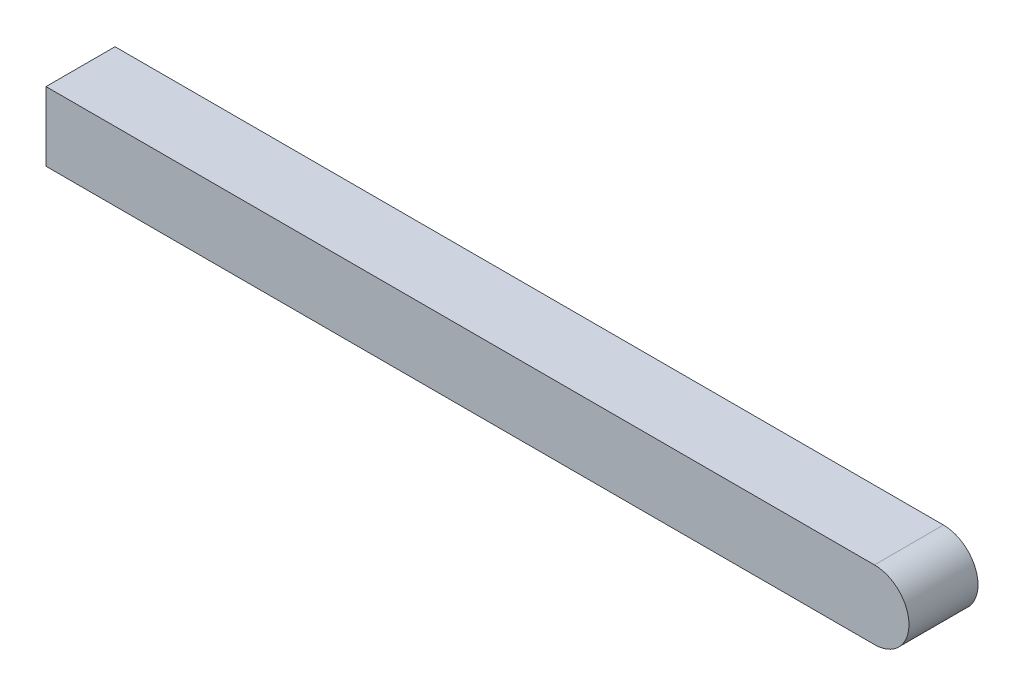
SolidWorks part; units mm, degrees
ref_plane "前视基准面" through (0, 0, 0) normal (0, 0, 1) x (1, 0, 0)
ref_plane "上视基准面" through (0, 0, 0) normal (0, 1, 0) x (1, 0, 0)
ref_plane "右视基准面" through (0, 0, 0) normal (1, 0, 0) x (0, 0, -1)
sketch "草图1" plane through (0, 0, 0) normal (0, 0, 1) x (1, 0, 0)
  line L1 (-11.1073, -0.4837) -> (0.8927, -0.4837)
  line L2 (-11.1073, -0.4837) -> (-11.1073, 0.5163)
  line L3 (-11.1073, 0.5163) -> (0.8927, 0.5163)
  arc A0 (0.8927, -0.4837) -> (0.8927, 0.5163) centre (0.8927, 0.0163) ccw
  point P0 (-5.1073, 0.0163)
  point P7 (0, 0)
  dimension "D1" = 1
  dimension "D2" = 1
  dimension "D3" = 12
extrude "凸台-拉伸1" add sketch "草图1" along normal blind 1 contours L1 A0 L3 L2
